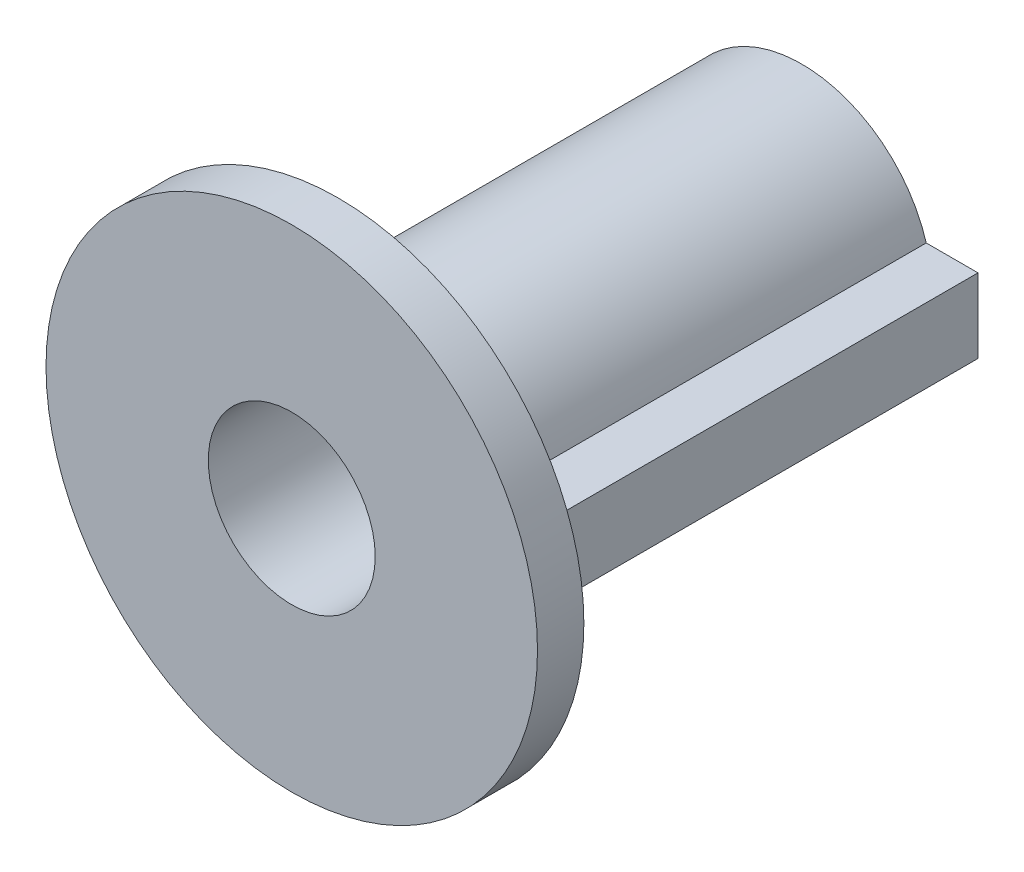
SolidWorks part; units mm, degrees
ref_plane "Front Plane" through (0, 0, 0) normal (0, 0, 1) x (1, 0, 0)
ref_plane "Top Plane" through (0, 0, 0) normal (0, 1, 0) x (1, 0, 0)
ref_plane "Right Plane" through (0, 0, 0) normal (1, 0, 0) x (0, 0, -1)
sketch "Sketch1" plane through (0, 0, 0) normal (0, 0, 1) x (1, 0, 0)
  line L0 (-30.3167, 9.2) -> (-29.2, 9.2)
  line L1 (-29.2, 9.2) -> (-29.2, 10.8)
  line L2 (-29.2, 10.8) -> (-30.3167, 10.8)
  line L3 (-30.1716, 9) -> (-29, 9)
  line L4 (-29, 9) -> (-29, 11)
  line L5 (-29, 11) -> (-30.1716, 11)
  line L6 (-30.1716, 9) -> (-29, 9)
  line L7 (-29, 9) -> (-29, 11)
  line L8 (-29, 11) -> (-30.1716, 11)
  arc A0 (-30.3167, 10.8) -> (-30.3167, 9.2) centre (-33, 10) ccw
  arc A1 (-30.1716, 11) -> (-30.1716, 9) centre (-33, 10) ccw
  arc A2 (-30.1716, 11) -> (-30.1716, 9) centre (-33, 10) ccw
  circle A3 centre (-33, 10) radius 1.75
  dimension "D3" = 3.5
  dimension "D1" = 0
  dimension "D2" = 0.2
extrude "Boss-Extrude1" add sketch "Sketch1" along normal up to surface (5 mm away) and the other way up to surface (5 mm away) contours L2 A0 L0 L1 A3
sketch "Sketch4" plane through (0, 0, 5) normal (0, 0, 1) x (1, 0, 0)
  line L0 (-29.2, 10.8) -> (-29.2, 9.2) construction
  circle A0 centre (-33, 10) radius 5.3
  circle A1 centre (-33, 10) radius 1.75 construction
  circle A2 centre (-33, 10) radius 1.75
  point P5 (-27.7, 10)
  dimension "D1" = 1.5
extrude "Boss-Extrude2" add sketch "Sketch4" along normal blind 1
sketch "Sketch2" plane through (0, 0, 6) normal (0, 0, 1) x (1, 0, 0)
  point P0 (-33, 10)
hole_wizard "M3 Clearance Hole1" positions "Sketch2" profile "Sketch3" hole size "M3" standard "ANSI Metric" end condition through all
sketch "Sketch3" plane through (-33, 10, 6) normal (1, 0, 0) x (0, -1, 0)
  line L0 (0, 0) -> (0, 11)
  line L1 (0, 11) -> (1.8, 11)
  line L2 (1.8, 11) -> (1.8, 0)
  line L5 (1.8, 0) -> (0, 0)
  line L11 (0, -6.35) -> (0, 107.95) construction
  dimension "Thru Hole Dia." = 3.6
  dimension "Thru Hole Depth" = 11
